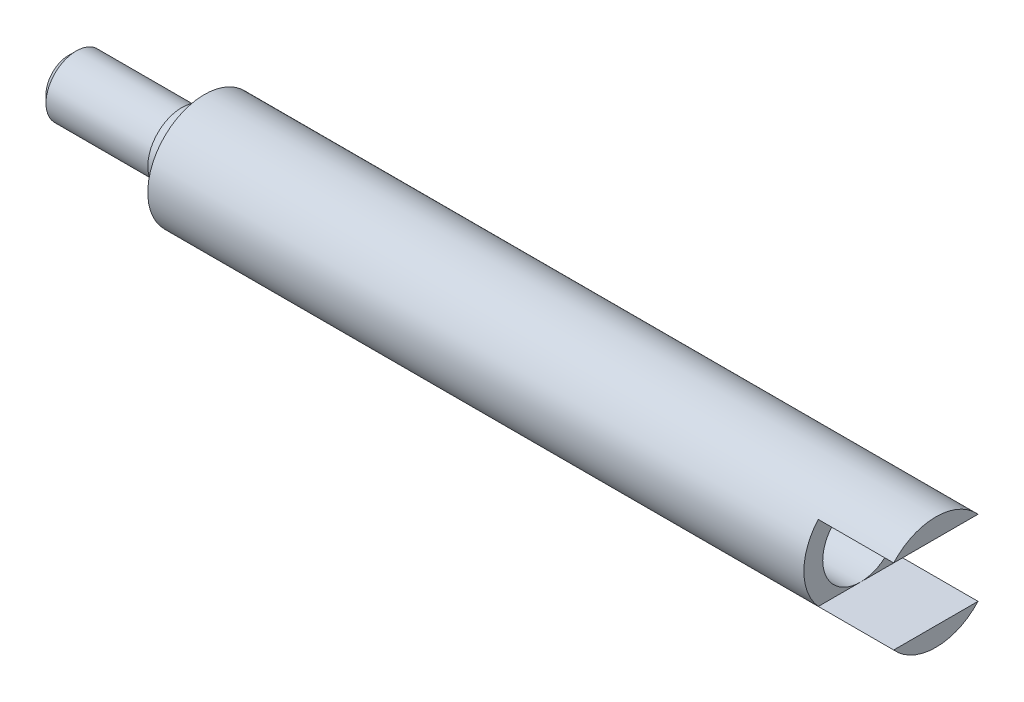
SolidWorks part; units mm, degrees
material "Сталь 3 ГОСТ 380-2005"
ref_plane "Спереди" through (0, 0, 0) normal (0, 0, 1) x (1, 0, 0)
ref_plane "Сверху" through (0, 0, 0) normal (0, 1, 0) x (1, 0, 0)
ref_plane "Справа" through (0, 0, 0) normal (1, 0, 0) x (0, 0, -1)
sketch "Эскиз1" plane through (0, 0, 0) normal (0, 0, 1) x (1, 0, 0)
  line L0 (0, 0) -> (-54.9968, 0) construction
  line L1 (0, 0) -> (0, 8)
  line L2 (0, 8) -> (30, 8)
  line L3 (30, 8) -> (30, 9)
  line L4 (30, 9) -> (36, 9)
  line L5 (36, 9) -> (36, 15)
  line L6 (230, 0) -> (0, 0)
  line L7 (36, 15) -> (230, 15)
  line L8 (230, 15) -> (230, 0)
  dimension "D1" = 16
  dimension "D2" = 18
  dimension "D3" = 30
  dimension "D4" = 6
  dimension "D5" = 30
  dimension "D6" = 230
revolve "Повернуть1" add sketch "Эскиз1" angle 360 about L0
chamfer "Фаска1" distance 2 angle 45 1 edges at (0, 0, -8)
sketch "Sketch1" plane through (230, 0, 0) normal (1, 0, 0) x (0, 0, -1)
  line L1 (15, 10) -> (-15, 10)
  line L2 (15, 10) -> (15, -10)
  line L3 (15, -10) -> (-15, -10)
  line L4 (-15, 10) -> (-15, -10)
  line L5 (0, -10) -> (0, 10) construction
  line L6 (15, 0) -> (-15, 0) construction
  circle A0 centre (0, 0) radius 15 construction
  point P0 (0, 0)
  dimension "D1" = 20
extrude "Extrude1" cut sketch "Sketch1" against normal blind 20
sketch "Sketch2" plane through (210, 0, 0) normal (1, 0, 0) x (0, 0, -1)
  circle A0 centre (0, 0) radius 10
  dimension "D1" = 20
extrude "Extrude3" cut sketch "Sketch2" against normal blind 160
